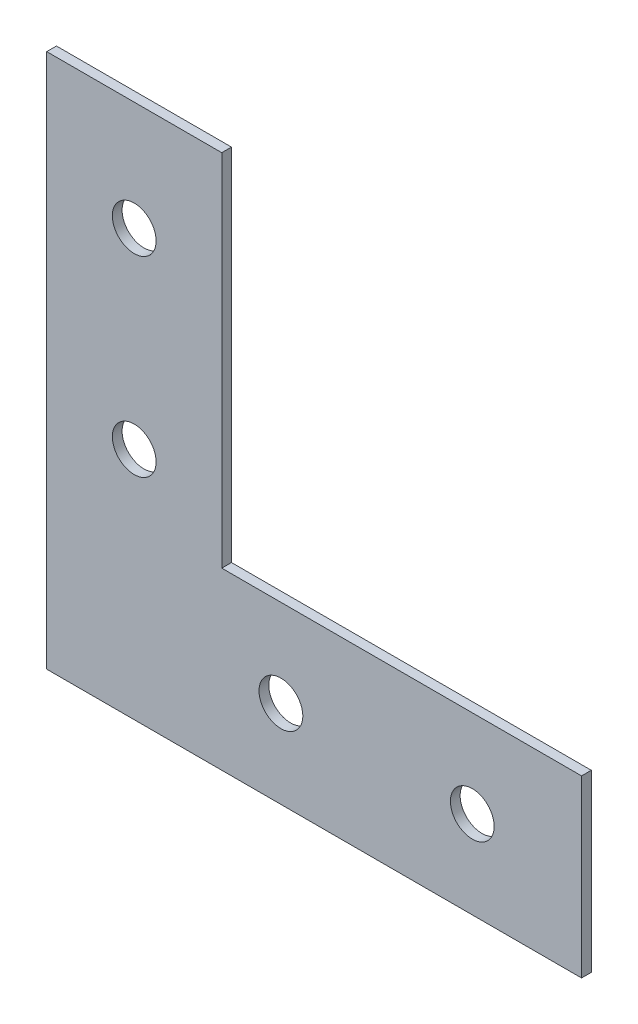
SolidWorks part; units mm, degrees
ref_plane "前视基准面" through (0, 0, 0) normal (0, 0, 1) x (1, 0, 0)
ref_plane "上视基准面" through (0, 0, 0) normal (0, 1, 0) x (1, 0, 0)
ref_plane "右视基准面" through (0, 0, 0) normal (1, 0, 0) x (0, 0, -1)
sketch "草图1" plane through (0, 0, 0) normal (0, 0, 1) x (1, 0, 0)
  line L1 (-18, -55) -> (18, -55)
  line L2 (-18, -55) -> (-18, 55)
  line L3 (-18, 55) -> (18, 55)
  line L4 (18, -55) -> (18, 55)
  line L5 (-18, -55) -> (18, 55) construction
  line L6 (-18, 55) -> (18, -55) construction
  point P0 (0, 0)
  dimension "D1" = 36
  dimension "D2" = 110
extrude "凸台-拉伸1" add sketch "草图1" along normal blind 2
sketch "草图2" plane through (0, 0, 2) normal (0, 0, 1) x (1, 0, 0)
  line L1 (-18, -55) -> (92, -55)
  line L2 (-18, -55) -> (-18, -19)
  line L3 (-18, -19) -> (92, -19)
  line L4 (92, -55) -> (92, -19)
  dimension "D1" = 36
  dimension "D2" = 110
extrude "凸台-拉伸2" add sketch "草图2" against normal blind 2
sketch "草图3" plane through (0, 0, 2) normal (0, 0, 1) x (1, 0, 0)
  line L0 (18, -19) -> (-18, -55) construction
  circle A0 centre (0, 32.5257) radius 4.5
  circle A1 centre (0, -6.8331) radius 4.5
  circle A2 centre (30.1669, -37) radius 4.5
  circle A3 centre (69.5257, -37) radius 4.5
  dimension "D1" = 9
  dimension "D2" = 9
extrude "切除-拉伸1" cut sketch "草图3" against normal through all
